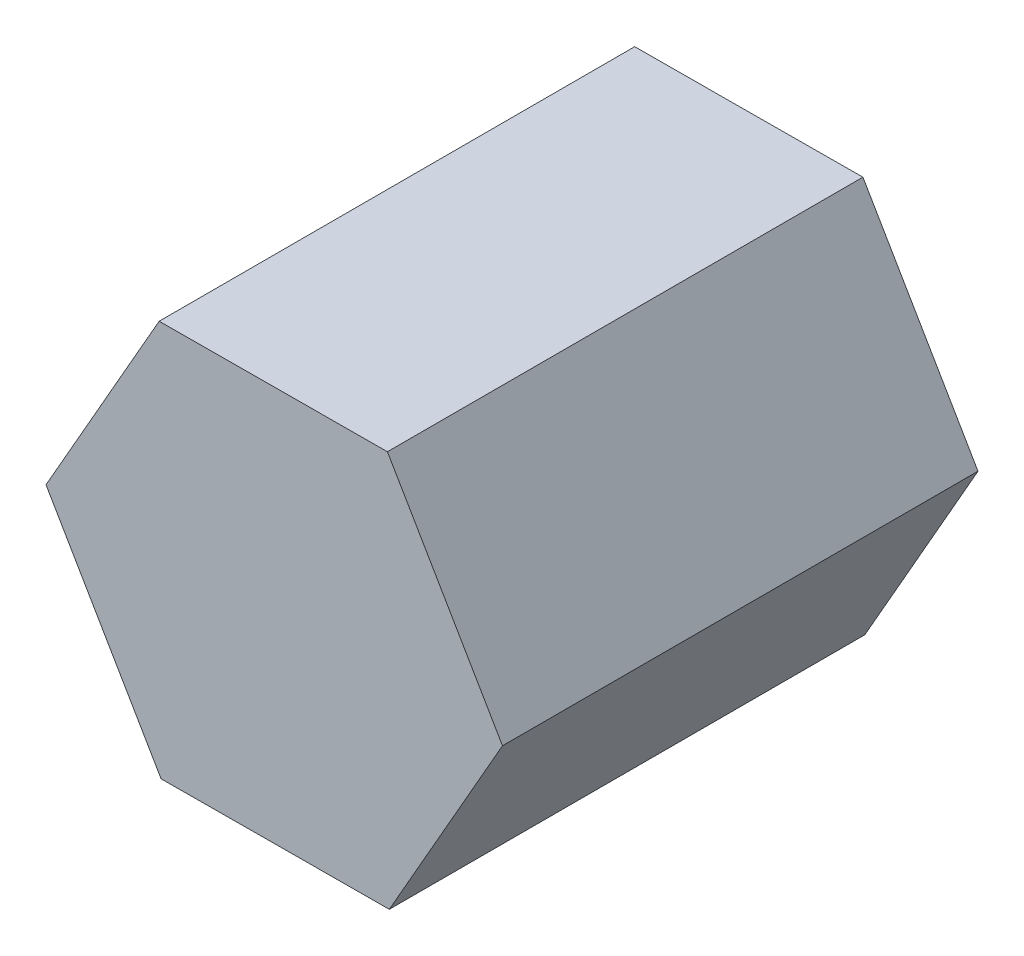
SolidWorks part; units mm, degrees
ref_plane "Alzado" through (0, 0, 0) normal (0, 0, 1) x (1, 0, 0)
ref_plane "Planta" through (0, 0, 0) normal (0, 1, 0) x (1, 0, 0)
ref_plane "Vista lateral" through (0, 0, 0) normal (1, 0, 0) x (0, 0, -1)
sketch "Croquis2" plane through (0, 0, 0) normal (0, 0, 1) x (1, 0, 0)
  line L1 (12.1007, -20.7265) -> (24, 0.1162)
  line L2 (24, 0.1162) -> (11.8993, 20.8427)
  line L3 (11.8993, 20.8427) -> (-12.1007, 20.7265)
  line L4 (-12.1007, 20.7265) -> (-24, -0.1162)
  line L5 (-24, -0.1162) -> (-11.8993, -20.8427)
  line L6 (-11.8993, -20.8427) -> (12.1007, -20.7265)
  circle A0 centre (0, 0) radius 20.7849 construction
  dimension "D1" = 48
extrude "Saliente-Extruir1" add sketch "Croquis2" along normal blind 50
sketch "Croquis3" plane through (0, 0, 0) normal (0, 0, -1) x (-1, 0, 0)
  circle A0 centre (0, 0) radius 5
  dimension "D1" = 10
extrude "Cortar-Extruir1" cut sketch "Croquis3" against normal blind 10
